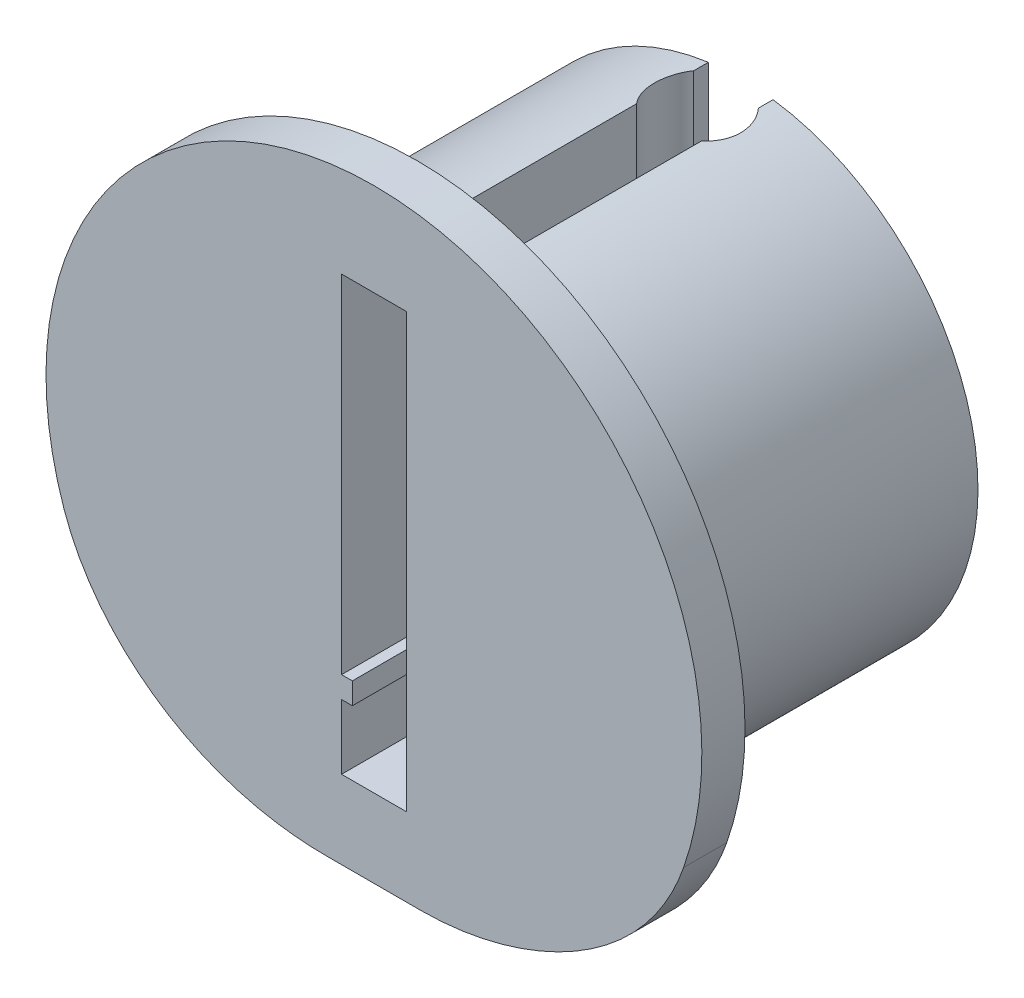
SolidWorks part; units mm, degrees
ref_plane "Front Plane" through (0, 0, 0) normal (0, 0, 1) x (1, 0, 0)
ref_plane "Top Plane" through (0, 0, 0) normal (0, 1, 0) x (1, 0, 0)
ref_plane "Right Plane" through (0, 0, 0) normal (1, 0, 0) x (0, 0, -1)
sketch "Sketch1" plane through (0, 0, 0) normal (0, 0, 1) x (1, 0, 0)
  line L0 (0, 0) -> (0, 11) construction
  line L1 (-1.5, 10.8972) -> (-1.5, -5.1833)
  line L2 (2, -5.1833) -> (-2, -5.1833)
  line L3 (2, -5.1833) -> (2, 10.8167)
  line L4 (2, 10.8167) -> (-2, 10.8167)
  line L5 (-2, -5.1833) -> (-2, 10.8167)
  line L6 (2, -5.1833) -> (-2, 10.8167) construction
  line L7 (2, 10.8167) -> (-2, -5.1833) construction
  line L8 (2, -5.1833) -> (-1, -5.1833)
  line L9 (2, -5.1833) -> (2, -6.1833)
  line L10 (2, -6.1833) -> (-1, -6.1833)
  line L11 (-1, -5.1833) -> (-1, -6.1833)
  line L12 (2, -6.1833) -> (-2, -6.1833)
  line L13 (2, -6.1833) -> (2, -9.1833)
  line L14 (2, -9.1833) -> (-2, -9.1833)
  line L15 (-2, -6.1833) -> (-2, -9.1833)
  line L16 (1.5, 10.8972) -> (1.5, -5.1833)
  line L17 (-1.5, -9.1833) -> (-1.5, -6.1833)
  line L18 (1.5, -5.1833) -> (1.5, -9.1833)
  circle A0 centre (0, 0) radius 11
  point P3 (0, 2.8167)
  dimension "D1" = 22
  dimension "D2" = 4
  dimension "D3" = 16
  dimension "D4" = 3
  dimension "D5" = 1
  dimension "D6" = 3
  dimension "D7" = 0.5
  dimension "D8" = 0.5
  dimension "D9" = 0.5
  dimension "D10" = 9.1833
extrude "Boss-Extrude1" add sketch "Sketch1" along normal blind 15 contours L5 A0 L3 L9 L13 L14 L15 L12 L11 L2 | L4 L16 L2 L3 | L2 L18 L10 L9 | L10 L18 L14 L13 | L14 L17 L12 L15 | L5 L2 L1 L4 | L4 A0 L16 | L1 A0 L4
sketch "Pin Hole sketch" plane through (0, 0, 0) normal (0, 1, 0) x (1, 0, 0)
  line L0 (-1.5, 0) -> (1.5, 0) construction
  line L1 (1.5, 0) -> (-1.5, 0) construction
  line L2 (0, -2) -> (0, 0) construction
  circle A0 centre (0, -2) radius 2
  dimension "D1" = 4
sketch "Sketch4" plane through (0, 0, 0) normal (0, 0, -1) x (-1, 0, 0)
  line L0 (-2, 10.8167) -> (-2, -9.1833)
  line L1 (-2, -9.1833) -> (2, -9.1833)
  line L2 (2, -9.1833) -> (2, -6.1833)
  line L3 (2, -6.1833) -> (1, -6.1833)
  line L4 (1, -6.1833) -> (1, -5.1833)
  line L5 (1, -5.1833) -> (2, -5.1833)
  line L6 (2, -5.1833) -> (2, 10.8167)
  line L7 (-2, 10.8167) -> (2, 10.8167) construction
  line L8 (-1.5, 10.8972) -> (-1.5, -9.1833)
  line L9 (1.5, 10.8972) -> (1.5, -9.1833)
  line L10 (-1.5, 10.8972) -> (-1.5, -9.1833) construction
  line L11 (1.5, 10.8972) -> (1.5, -5.1833) construction
  circle A0 centre (0, 0) radius 11
  dimension "D1" = 22
  dimension "D2" = 0.5
  dimension "D3" = 0.5
  dimension "D4" = 0.5
  dimension "D5" = 3
  dimension "D6" = 20
  dimension "D7" = 9.1833
  dimension "D8" = 1
sketch "Sketch5" plane through (0, 0, 0) normal (0, 0, -1) x (-1, 0, 0)
  line L0 (-11, 0) -> (11, 0) construction
  line L1 (-6, 1.5) -> (-4, -1.5) construction
  line L2 (-6, 1.5) -> (-4, 1.5)
  line L3 (-6, 1.5) -> (-6, -1.5)
  line L4 (-6, -1.5) -> (-4, -1.5)
  line L5 (-4, 1.5) -> (-4, -1.5)
  line L6 (4, 1.5) -> (6, 1.5)
  line L7 (4, 1.5) -> (4, -1.5)
  line L8 (4, -1.5) -> (6, -1.5)
  line L9 (6, 1.5) -> (6, -1.5)
  line L10 (4, 1.5) -> (6, -1.5) construction
  line L11 (-6, -1.5) -> (-4, 1.5) construction
  line L12 (-11, 0) -> (-5, 0) construction
  line L13 (4, -1.5) -> (6, 1.5) construction
  line L14 (5, 0) -> (11, 0) construction
  circle A0 centre (0, 0) radius 11
  point P13 (-5, 0)
  dimension "D1" = 22
  dimension "D2" = 2
  dimension "D3" = 3
  dimension "D4" = 2
  dimension "D5" = 3
  dimension "D6" = 6
  dimension "D7" = 6
extrude "Cut-Extrude1" cut sketch "Sketch5" against normal blind 2 contours L5 L2 L3 L4 | L9 L6 L7 L8
sketch "Sketch3" plane through (0, 0, 15) normal (0, 0, 1) x (1, 0, 0)
  line L0 (0, 0) -> (0, -11) construction
  line L1 (0, -12.8125) -> (2.2, -12.8125) construction
  line L2 (2.2, -12.8125) -> (-2.2, -12.8125)
  line L3 (0, -11) -> (0, -13) construction
  line L4 (-14.3541, -5) -> (14.3541, -5)
  line L5 (-1.5, 10.8972) -> (1.5, 10.8972)
  line L6 (0, -12.8125) -> (0, -15.2) construction
  circle A0 centre (0, 0) radius 11
  circle A1 centre (0, 0) radius 15.2
  arc A2 (-1.5, 10.8972) -> (1.5, 10.8972) centre (0, 0) ccw construction
  circle A3 centre (0, 0) radius 13
  spline S0 degree 3 poles (-14.3541, -5) (-12.8633, -9.2797) (-8.2667, -12.8125) (-2.2, -12.8125) knots 0 0 0 0 1 1 1 1
  spline S1 degree 3 poles (2.2, -12.8125) (6.7319, -12.8125) (12.5051, -10.3082) (14.3541, -5) knots 0 0 0 0 1 1 1 1
  arc M8 (-1.5, 10.8972) -> (1.5, 10.8972) centre (0, 0) ccw
  line M10 (1.5, -9.1833) -> (-1.5, -9.1833)
  line M12 (-1.5, -6.1833) -> (-1, -6.1833)
  line M13 (-1, -6.1833) -> (-1, -5.1833)
  line M14 (-1, -5.1833) -> (-1.5, -5.1833)
  line M27 (1.5, 10.8972) -> (1.5, -9.1833)
  line M28 (-1.5, -9.1833) -> (-1.5, -6.1833)
  line M29 (-1.5, -5.1833) -> (-1.5, 10.8972)
  dimension "D3" = 2
  dimension "D1" = 30.4
  dimension "D4" = 5
  dimension "D5" = 2.3875
  dimension "D2" = 2.2
extrude "Boss-Extrude2" add sketch "Sketch3" along normal blind 2 contours L4 S0 A3 | L4 A3 L2 M8 | A3 S1 L4 | L4 M8 M27 M10 M28 M12 M13 M14 M29 | L4 M27 M8 | L4 M8 M29 | L4 A3 A0 M8 | A3 L4 A1 | L5 A0
sketch "Sketch6" plane through (0, 0, 17) normal (0, 0, 1) x (1, 0, 0)
  line L0 (-14.3541, -5) -> (14.3541, 5) construction
  line L1 (14.3541, -5) -> (-14.3541, 5) construction
  line L2 (0, 0) -> (0, -12.8125) construction
  line L3 (2.2, -12.8125) -> (-2.2, -12.8125) construction
  line L4 (0, 0) -> (-10.8329, -1.9101)
  line L5 (-11.8928, 0.4153) -> (0, 0)
  line L6 (0, 0) -> (-15.2, 0) construction
  line L7 (-10.8329, -1.9101) -> (-11.7192, -2.0664)
  circle A0 centre (0, 0) radius 11
  arc A1 (14.3541, -5) -> (-14.3541, -5) centre (0, 0) ccw construction
  arc A2 (-11.7192, -2.0664) -> (-11.8928, 0.4153) centre (0, 0) cw
  dimension "D1" = 80
  dimension "D2" = 70.795
  dimension "D3" = 9.205
  dimension "D4" = 0.9
  dimension "D5" = 12
extrude "Stick Outs" add sketch "Sketch6" against normal blind 0.8 from surface at -2 contours A2 L7 A0 L5 starting at face at (-3.0385, -3.8562, 15)
mirror "Mirror1" about plane through (0, 0, 0) normal (1, 0, 0) of "Stick Outs"
extrude "Pin hole" cut sketch "Pin Hole sketch" against normal up to surface (5.1833 mm away) and the other way through all up to face at (-1.25, -5.1833, 8.5)
equation "\"ET_circle_diam\"= 0.3mm'add to diameter of outer circle"
